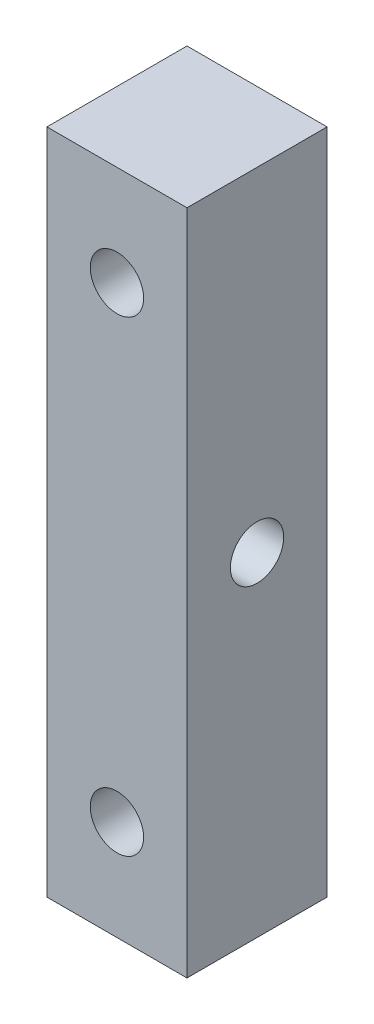
SolidWorks part; units mm, degrees
ref_plane "Front Plane" through (0, 0, 0) normal (0, 0, 1) x (1, 0, 0)
ref_plane "Top Plane" through (0, 0, 0) normal (0, 1, 0) x (1, 0, 0)
ref_plane "Right Plane" through (0, 0, 0) normal (1, 0, 0) x (0, 0, -1)
sketch "Sketch1" plane through (0, 0, 0) normal (0, 1, 0) x (1, 0, 0)
  line L1 (-10.5, -10.5) -> (10.5, -10.5)
  line L2 (-10.5, -10.5) -> (-10.5, 10.5)
  line L3 (-10.5, 10.5) -> (10.5, 10.5)
  line L4 (10.5, -10.5) -> (10.5, 10.5)
  line L5 (-10.5, -10.5) -> (10.5, 10.5) construction
  line L6 (-10.5, 10.5) -> (10.5, -10.5) construction
  point P0 (0, 0)
  dimension "D1" = 21
  dimension "D2" = 21
extrude "Boss-Extrude1" add sketch "Sketch1" along normal blind 100
sketch "Sketch2" plane through (0, 0, 10.5) normal (0, 0, 1) x (1, 0, 0)
  line L0 (-10.5, 100) -> (10.5, 100) construction
  line L1 (-10.5, 0) -> (10.5, 0) construction
  circle A0 centre (0, 85) radius 4
  circle A1 centre (0, 15) radius 4
  dimension "D1" = 8
  dimension "D2" = 8
  dimension "D3" = 15
  dimension "D4" = 15
extrude "Cut-Extrude1" cut sketch "Sketch2" against normal through all
sketch "Sketch4" plane through (10.5, 0, 0) normal (1, 0, 0) x (0, 0, -1)
  line L2 (-10.5, 0) -> (10.5, 0) construction
  circle A1 centre (0, 50) radius 4
  dimension "D1" = 50
  dimension "D2" = 8
extrude "Cut-Extrude2" cut sketch "Sketch4" against normal through all
